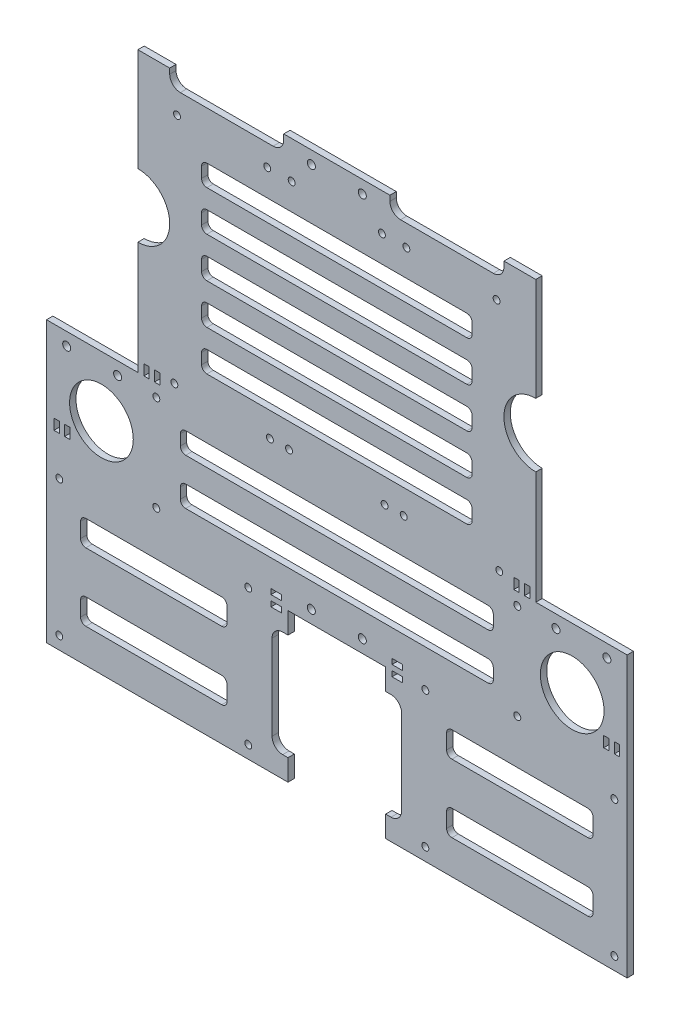
SolidWorks part; units mm, degrees
material "Oak"
ref_plane "Front Plane" through (0, 0, 0) normal (0, 0, 1) x (1, 0, 0)
ref_plane "Top Plane" through (0, 0, 0) normal (0, 1, 0) x (1, 0, 0)
ref_plane "Right Plane" through (0, 0, 0) normal (1, 0, 0) x (0, 0, -1)
sketch "Sketch1" plane through (0, 0, 0) normal (0, 0, 1) x (1, 0, 0)
  line L1 (0, 0) -> (273.4, 0)
  line L2 (0, 0) -> (0, -263.4)
  line L3 (0, -263.4) -> (273.4, -263.4)
  line L4 (273.4, 0) -> (273.4, -263.4)
  dimension "D1" = 273.4
  dimension "D2" = 263.4
extrude "Boss-Extrude1" add sketch "Sketch1" along normal blind 3
sketch "Sketch2" plane through (0, 0, 3) normal (0, 0, 1) x (1, 0, 0)
  line L1 (0, 0) -> (43, 0)
  line L2 (0, 0) -> (0, -131.64)
  line L3 (0, -131.64) -> (43, -131.64)
  line L4 (43, 0) -> (43, -131.64)
  line L9 (273.4, 0) -> (230.4, 0)
  line L10 (273.4, 0) -> (273.4, -131.64)
  line L11 (273.4, -131.64) -> (230.4, -131.64)
  line L12 (230.4, 0) -> (230.4, -131.64)
  dimension "D1" = 43
  dimension "D2" = 131.64
  dimension "D5" = 43
  dimension "D6" = 131.64
extrude "Cut-Extrude1" cut sketch "Sketch2" against normal through all
sketch "Sketch3" plane through (0, 0, 0) normal (0, 0, -1) x (-1, 0, 0)
  line L0 (0, -263.4) -> (-273.4, -263.4) construction
  line L1 (-159.7, -193.4) -> (-113.7, -193.4)
  line L2 (-159.7, -193.4) -> (-159.7, -263.4)
  line L3 (-159.7, -263.4) -> (-113.7, -263.4)
  line L4 (-113.7, -193.4) -> (-113.7, -263.4)
  line L5 (-273.4, -263.4) -> (-273.4, -131.64) construction
  dimension "D1" = 46
  dimension "D2" = 70
  dimension "D3" = 113.7
extrude "Cut-Extrude2" cut sketch "Sketch3" against normal through all
hole_wizard "#4 Clearance Hole1" positions "Sketch5" profile "Sketch6" hole size "#4" standard "ANSI Inch" end condition up to next
sketch "Sketch5" plane through (0, 0, 0) normal (0, 0, -1) x (-1, 0, 0)
  line L4 (-159.7, -263.4) -> (-273.4, -263.4) construction
  line L8 (-221.7, -137.5) -> (-51.7, -137.5) construction
  line L9 (-221.7, -137.5) -> (-221.7, -182.5) construction
  line L10 (-221.7, -182.5) -> (-51.7, -182.5) construction
  line L11 (-51.7, -137.5) -> (-51.7, -182.5) construction
  line L31 (-157.95, -17.5) -> (-115.45, -17.5) construction
  line L32 (-159.2, -127.5) -> (-114.2, -127.5) construction
  line L35 (-136.7, 0) -> (-136.7, -193.4) construction
  line L36 (-230.4, 0) -> (-43, 0) construction
  line L37 (-113.7, -193.4) -> (-159.7, -193.4) construction
  line L38 (-103.95, -17.5) -> (-61.45, -17.5) construction
  line L39 (-105.2, -127.5) -> (-60.2, -127.5) construction
  line L40 (-211.95, -17.5) -> (-169.45, -17.5) construction
  line L41 (-213.2, -127.5) -> (-168.2, -127.5) construction
  line L42 (0, -131.64) -> (0, -263.4) construction
  line L43 (-273.4, -263.4) -> (-273.4, -131.64) construction
  point P0 (-267.4, -257.4)
  point P2 (-267.4, -193.4)
  point P4 (-178.4, -193.4)
  point P6 (-178.4, -257.4)
  point P8 (-95, -257.4)
  point P10 (-95, -193.4)
  point P12 (-6, -193.4)
  point P14 (-6, -257.4)
  point P16 (-221.7, -137.5)
  point P18 (-221.7, -182.5)
  point P20 (-51.7, -137.5)
  point P22 (-51.7, -182.5)
  point P276 (-115.45, -17.5)
  point P277 (-157.95, -17.5)
  point P278 (-114.2, -127.5)
  point P279 (-159.2, -127.5)
  point P302 (-136.7, -17.5)
  point P306 (-136.7, -127.5)
  point P311 (-61.45, -17.5)
  point P312 (-103.95, -17.5)
  point P313 (-60.2, -127.5)
  point P314 (-105.2, -127.5)
  point P320 (-169.45, -17.5)
  point P321 (-211.95, -17.5)
  point P322 (-168.2, -127.5)
  point P323 (-213.2, -127.5)
  point P330 (-136.7, -137.5)
  dimension "D1" = 89
  dimension "D2" = 6
  dimension "D3" = 64
  dimension "D4" = 6
  dimension "D5" = 89
  dimension "D6" = 64
  dimension "D7" = 6
  dimension "D8" = 45
  dimension "D9" = 170
  dimension "D10" = 42.5
  dimension "D11" = 45
  dimension "D12" = 110
  dimension "D13" = 17.5
  dimension "D14" = 2
  dimension "D15" = 10
sketch "Sketch6" plane through (267.4, -257.4, 0) normal (1, 0, 0) x (0, 1, 0)
  line L0 (0, 0) -> (0, 3)
  line L1 (0, 3) -> (1.6319, 3)
  line L2 (1.6319, 3) -> (1.632, 0)
  line L5 (1.632, 0) -> (0, 0)
  line L11 (0, -6.35) -> (0, 107.95) construction
  dimension "Thru Hole Dia." = 3.2639
  dimension "Thru Hole Depth" = 3
sketch "Sketch4" plane through (0, 0, 3) normal (0, 0, 1) x (1, 0, 0)
  line L0 (230.4, 0) -> (43, 0) construction
  line L1 (58, 0) -> (111.7, 0)
  line L2 (58, 0) -> (58, -2.5)
  line L3 (63, -7.5) -> (106.7, -7.5)
  line L4 (111.7, 0) -> (111.7, -2.5)
  line L6 (43, -131.64) -> (43, 0) construction
  line L7 (159.7, -193.4) -> (159.7, -263.4) construction
  line L13 (0, -131.64) -> (0, -263.4) construction
  line L15 (43, -48.5) -> (43, -78.5)
  line L16 (230.4, -48.5) -> (230.4, -78.5)
  line L17 (210.4, -7.5) -> (166.7, -7.5)
  line L18 (161.7, 0) -> (161.7, -2.5)
  line L19 (215.4, 0) -> (161.7, 0)
  line L20 (215.4, 0) -> (215.4, -2.5)
  line L21 (51.7, -137.5) -> (51.7, -182.5) construction
  line L22 (51.7, -160) -> (0, -160) construction
  line L23 (159.7, -203.4) -> (162.2, -203.4)
  line L24 (159.7, -203.4) -> (159.7, -253.4)
  line L25 (159.7, -253.4) -> (162.2, -253.4)
  line L26 (167.2, -208.4) -> (167.2, -248.4)
  line L27 (159.7, -263.4) -> (273.4, -263.4) construction
  line L28 (136.7, -193.4) -> (136.7, -263.4411) construction
  line L29 (113.7, -193.4) -> (159.7, -193.4) construction
  line L30 (106.2, -208.4) -> (106.2, -248.4)
  line L31 (113.7, -253.4) -> (111.2, -253.4)
  line L32 (113.7, -203.4) -> (113.7, -253.4)
  line L33 (113.7, -203.4) -> (111.2, -203.4)
  line L34 (113.7, -263.4) -> (113.7, -193.4) construction
  line L35 (105.7, -195.9) -> (110.7, -195.9)
  line L36 (105.7, -195.9) -> (105.7, -193.4)
  line L37 (105.7, -193.4) -> (110.7, -193.4)
  line L38 (110.7, -195.9) -> (110.7, -193.4)
  line L39 (105.7, -190.9) -> (110.7, -190.9)
  line L40 (105.7, -190.9) -> (105.7, -188.4)
  line L41 (105.7, -188.4) -> (110.7, -188.4)
  line L42 (110.7, -190.9) -> (110.7, -188.4)
  line L51 (162.7, -190.9) -> (162.7, -188.4)
  line L52 (167.7, -188.4) -> (162.7, -188.4)
  line L53 (167.7, -190.9) -> (167.7, -188.4)
  line L54 (167.7, -190.9) -> (162.7, -190.9)
  line L55 (162.7, -195.9) -> (162.7, -193.4)
  line L56 (167.7, -193.4) -> (162.7, -193.4)
  line L57 (167.7, -195.9) -> (167.7, -193.4)
  line L58 (167.7, -195.9) -> (162.7, -195.9)
  line L64 (262.4, -170) -> (262.4, -175)
  line L69 (3.5, -170) -> (6, -170)
  line L70 (3.5, -170) -> (3.5, -175)
  line L71 (3.5, -175) -> (6, -175)
  line L72 (6, -170) -> (6, -175)
  line L73 (8.5, -170) -> (11, -170)
  line L74 (8.5, -170) -> (8.5, -175)
  line L75 (8.5, -175) -> (11, -175)
  line L76 (11, -170) -> (11, -175)
  line L77 (264.9, -175) -> (262.4, -175)
  line L78 (264.9, -170) -> (264.9, -175)
  line L79 (264.9, -170) -> (262.4, -170)
  line L80 (267.4, -170) -> (267.4, -175)
  line L81 (269.9, -175) -> (267.4, -175)
  line L82 (269.9, -170) -> (269.9, -175)
  line L83 (269.9, -170) -> (267.4, -170)
  line L84 (45.8282, -126.64) -> (48.3282, -126.64)
  line L85 (45.8282, -126.64) -> (45.8282, -131.64)
  line L86 (45.8282, -131.64) -> (48.3282, -131.64)
  line L87 (48.3282, -126.64) -> (48.3282, -131.64)
  line L88 (50.8282, -126.64) -> (53.3282, -126.64)
  line L89 (50.8282, -126.64) -> (50.8282, -131.64)
  line L90 (50.8282, -131.64) -> (53.3282, -131.64)
  line L91 (53.3282, -126.64) -> (53.3282, -131.64)
  line L92 (0, -131.64) -> (43, -131.64) construction
  line L93 (220.0718, -126.64) -> (220.0718, -131.64)
  line L94 (222.5718, -131.64) -> (220.0718, -131.64)
  line L95 (222.5718, -126.64) -> (222.5718, -131.64)
  line L96 (222.5718, -126.64) -> (220.0718, -126.64)
  line L97 (225.0718, -126.64) -> (225.0718, -131.64)
  line L98 (227.5718, -131.64) -> (225.0718, -131.64)
  line L99 (227.5718, -126.64) -> (227.5718, -131.64)
  line L100 (227.5718, -126.64) -> (225.0718, -126.64)
  arc A0 (43, -48.5) -> (43, -78.5) centre (43, -63.5) cw
  circle A1 centre (25.85, -160) radius 15
  circle A2 centre (247.55, -160) radius 15
  arc A3 (230.4, -48.5) -> (230.4, -78.5) centre (230.4, -63.5) ccw
  arc A4 (58, -2.5) -> (63, -7.5) centre (63, -2.5) ccw
  arc A5 (106.7, -7.5) -> (111.7, -2.5) centre (106.7, -2.5) ccw
  arc A6 (166.7, -7.5) -> (161.7, -2.5) centre (166.7, -2.5) cw
  arc A7 (210.4, -7.5) -> (215.4, -2.5) centre (210.4, -2.5) ccw
  arc A10 (162.2, -253.4) -> (167.2, -248.4) centre (162.2, -248.4) ccw
  arc A11 (162.2, -203.4) -> (167.2, -208.4) centre (162.2, -208.4) cw
  arc A12 (111.2, -203.4) -> (106.2, -208.4) centre (111.2, -208.4) ccw
  arc A13 (111.2, -253.4) -> (106.2, -248.4) centre (111.2, -248.4) cw
  point P39 (58, -7.5)
  point P42 (111.7, -7.5)
  point P45 (161.7, -7.5)
  point P48 (215.4, -7.5)
  point P54 (167.2, -203.4)
  point P67 (106.2, -203.4)
  dimension "D4" = 5
  dimension "D7" = 15
  dimension "D8" = 30
  dimension "D5" = 2.5
  dimension "D10" = 5
  dimension "D1" = 7.5
  dimension "D2" = 15
  dimension "D3" = 50
  dimension "D6" = 63.5
  dimension "D9" = 10
  dimension "D11" = 2.5
  dimension "D12" = 2.5
  dimension "D13" = 5
  dimension "D14" = 3
  dimension "D15" = 2.5
  dimension "D16" = 2.5
  dimension "D17" = 2.5
  dimension "D18" = 5
  dimension "D19" = 3.5
  dimension "D20" = 2.5
extrude "Cut-Extrude3" cut sketch "Sketch4" against normal up to next
hole_wizard "#6 Clearance Hole1" positions "Sketch7" profile "Sketch8" hole size "#6" standard "ANSI Inch" end condition up to next
sketch "Sketch7" plane through (0, 0, 3) normal (0, 0, 1) x (1, 0, 0)
  line L1 (111.7, -2.5) -> (111.7, 0) construction
  line L4 (113.7, -263.4) -> (113.7, -253.4) construction
  line L5 (0, -131.64) -> (43, -131.64) construction
  line L6 (113.7, -193.4) -> (159.7, -193.4) construction
  line L7 (230.4, -131.64) -> (273.4, -131.64) construction
  line L8 (161.7, 0) -> (111.7, 0) construction
  line L9 (0, -131.64) -> (0, -263.4) construction
  line L10 (273.4, -263.4) -> (273.4, -131.64) construction
  point P0 (124.7, -6)
  point P2 (148.7, -6)
  point P4 (9.5, -137.64)
  point P6 (33.5, -137.64)
  point P8 (124.7, -187.4)
  point P10 (148.7, -187.4)
  point P20 (263.9, -137.64)
  point P22 (239.9, -137.64)
  dimension "D1" = 24
  dimension "D2" = 24
  dimension "D3" = 24
  dimension "D4" = 24
  dimension "D5" = 13
  dimension "D6" = 11
  dimension "D7" = 6
  dimension "D8" = 6
  dimension "D9" = 6
  dimension "D10" = 6
  dimension "D11" = 9.5
  dimension "D12" = 9.5
sketch "Sketch8" plane through (124.7, -6, 3) normal (1, 0, 0) x (0, -1, 0)
  line L0 (0, 0) -> (0, 3)
  line L1 (0, 3) -> (1.8986, 3)
  line L2 (1.8986, 3) -> (1.8986, 0)
  line L5 (1.8986, 0) -> (0, 0)
  line L11 (0, -6.35) -> (0, 107.95) construction
  dimension "Thru Hole Dia." = 3.7973
  dimension "Thru Hole Depth" = 3
sketch "Sketch10" plane through (0, 0, 3) normal (0, 0, 1) x (1, 0, 0)
  line L0 (43, -48.5) -> (43, 0) construction
  line L1 (75.5, -30) -> (197.9, -30)
  line L2 (73, -32.5) -> (73, -37.5)
  line L3 (75.5, -40) -> (197.9, -40)
  line L4 (200.4, -32.5) -> (200.4, -37.5)
  line L5 (230.4, 0) -> (230.4, -48.5) construction
  line L6 (161.7, 0) -> (111.7, 0) construction
  line L7 (73, -51.5) -> (73, -56.5)
  line L8 (75.5, -49) -> (197.9, -49)
  line L9 (200.4, -51.5) -> (200.4, -56.5)
  line L10 (75.5, -59) -> (197.9, -59)
  line L11 (73, -70.5) -> (73, -75.5)
  line L12 (75.5, -68) -> (197.9, -68)
  line L13 (200.4, -70.5) -> (200.4, -75.5)
  line L14 (75.5, -78) -> (197.9, -78)
  line L15 (73, -89.5) -> (73, -94.5)
  line L16 (75.5, -87) -> (197.9, -87)
  line L17 (200.4, -89.5) -> (200.4, -94.5)
  line L18 (75.5, -97) -> (197.9, -97)
  line L19 (73, -108.5) -> (73, -113.5)
  line L20 (75.5, -106) -> (197.9, -106)
  line L21 (200.4, -108.5) -> (200.4, -113.5)
  line L22 (75.5, -116) -> (197.9, -116)
  line L23 (73, -32.5) -> (73, -51.5) construction
  line L24 (43, -131.64) -> (43, -78.5) construction
  line L25 (18.5, -203.4) -> (82.5, -203.4)
  line L26 (16, -205.9) -> (16, -212.9)
  line L27 (18.5, -215.4) -> (82.5, -215.4)
  line L28 (85, -205.9) -> (85, -212.9)
  line L29 (65.5, -144.14) -> (207.9, -144.14)
  line L30 (63, -146.64) -> (63, -151.64)
  line L31 (65.5, -154.14) -> (207.9, -154.14)
  line L32 (210.4, -146.64) -> (210.4, -151.64)
  line L33 (230.4, -78.5) -> (230.4, -131.64) construction
  line L34 (0, -131.64) -> (43, -131.64) construction
  line L35 (51.7, -137.5) -> (51.7, -182.5) construction
  line L36 (51.7, -160) -> (225.1949, -160) construction
  line L37 (65.5, -165.86) -> (207.9, -165.86)
  line L38 (210.4, -173.36) -> (210.4, -168.36)
  line L39 (65.5, -175.86) -> (207.9, -175.86)
  line L40 (63, -173.36) -> (63, -168.36)
  line L41 (6, -193.4) -> (95, -193.4) construction
  line L42 (95, -193.4) -> (95, -257.4) construction
  line L43 (95, -257.4) -> (6, -257.4) construction
  line L44 (6, -257.4) -> (6, -193.4) construction
  line L45 (6, -225.4) -> (95, -225.4) construction
  line L46 (18.5, -235.4) -> (82.5, -235.4)
  line L47 (85, -244.9) -> (85, -237.9)
  line L48 (18.5, -247.4) -> (82.5, -247.4)
  line L49 (16, -244.9) -> (16, -237.9)
  line L50 (136.7, -193.4) -> (136.7, -279.5372) construction
  line L51 (113.7, -193.4) -> (159.7, -193.4) construction
  line L52 (254.9, -215.4) -> (190.9, -215.4)
  line L53 (188.4, -205.9) -> (188.4, -212.9)
  line L54 (254.9, -203.4) -> (190.9, -203.4)
  line L55 (257.4, -205.9) -> (257.4, -212.9)
  line L56 (257.4, -244.9) -> (257.4, -237.9)
  line L57 (254.9, -247.4) -> (190.9, -247.4)
  line L58 (188.4, -244.9) -> (188.4, -237.9)
  line L59 (254.9, -235.4) -> (190.9, -235.4)
  arc A0 (197.9, -30) -> (200.4, -32.5) centre (197.9, -32.5) cw
  arc A1 (197.9, -40) -> (200.4, -37.5) centre (197.9, -37.5) ccw
  arc A2 (73, -37.5) -> (75.5, -40) centre (75.5, -37.5) ccw
  arc A3 (75.5, -30) -> (73, -32.5) centre (75.5, -32.5) ccw
  arc A4 (75.5, -49) -> (73, -51.5) centre (75.5, -51.5) ccw
  arc A5 (73, -56.5) -> (75.5, -59) centre (75.5, -56.5) ccw
  arc A6 (197.9, -49) -> (200.4, -51.5) centre (197.9, -51.5) cw
  arc A7 (197.9, -59) -> (200.4, -56.5) centre (197.9, -56.5) ccw
  arc A8 (75.5, -68) -> (73, -70.5) centre (75.5, -70.5) ccw
  arc A9 (73, -75.5) -> (75.5, -78) centre (75.5, -75.5) ccw
  arc A10 (197.9, -68) -> (200.4, -70.5) centre (197.9, -70.5) cw
  arc A11 (197.9, -78) -> (200.4, -75.5) centre (197.9, -75.5) ccw
  arc A12 (75.5, -87) -> (73, -89.5) centre (75.5, -89.5) ccw
  arc A13 (73, -94.5) -> (75.5, -97) centre (75.5, -94.5) ccw
  arc A14 (197.9, -87) -> (200.4, -89.5) centre (197.9, -89.5) cw
  arc A15 (197.9, -97) -> (200.4, -94.5) centre (197.9, -94.5) ccw
  arc A16 (75.5, -106) -> (73, -108.5) centre (75.5, -108.5) ccw
  arc A17 (73, -113.5) -> (75.5, -116) centre (75.5, -113.5) ccw
  arc A18 (197.9, -106) -> (200.4, -108.5) centre (197.9, -108.5) cw
  arc A19 (197.9, -116) -> (200.4, -113.5) centre (197.9, -113.5) ccw
  arc A20 (63, -151.64) -> (65.5, -154.14) centre (65.5, -151.64) ccw
  arc A21 (207.9, -154.14) -> (210.4, -151.64) centre (207.9, -151.64) ccw
  arc A22 (207.9, -144.14) -> (210.4, -146.64) centre (207.9, -146.64) cw
  arc A23 (65.5, -144.14) -> (63, -146.64) centre (65.5, -146.64) ccw
  arc A24 (207.9, -165.86) -> (210.4, -168.36) centre (207.9, -168.36) cw
  arc A25 (207.9, -175.86) -> (210.4, -173.36) centre (207.9, -173.36) ccw
  arc A26 (63, -168.36) -> (65.5, -165.86) centre (65.5, -168.36) cw
  arc A27 (65.5, -175.86) -> (63, -173.36) centre (65.5, -173.36) cw
  arc A28 (16, -212.9) -> (18.5, -215.4) centre (18.5, -212.9) ccw
  arc A29 (82.5, -215.4) -> (85, -212.9) centre (82.5, -212.9) ccw
  arc A30 (85, -205.9) -> (82.5, -203.4) centre (82.5, -205.9) ccw
  arc A31 (18.5, -203.4) -> (16, -205.9) centre (18.5, -205.9) ccw
  arc A32 (82.5, -235.4) -> (85, -237.9) centre (82.5, -237.9) cw
  arc A33 (85, -244.9) -> (82.5, -247.4) centre (82.5, -244.9) cw
  arc A34 (16, -237.9) -> (18.5, -235.4) centre (18.5, -237.9) cw
  arc A35 (18.5, -247.4) -> (16, -244.9) centre (18.5, -244.9) cw
  arc A36 (190.9, -215.4) -> (188.4, -212.9) centre (190.9, -212.9) cw
  arc A37 (188.4, -205.9) -> (190.9, -203.4) centre (190.9, -205.9) cw
  arc A38 (257.4, -212.9) -> (254.9, -215.4) centre (254.9, -212.9) cw
  arc A39 (254.9, -203.4) -> (257.4, -205.9) centre (254.9, -205.9) cw
  arc A40 (257.4, -237.9) -> (254.9, -235.4) centre (254.9, -237.9) ccw
  arc A41 (254.9, -247.4) -> (257.4, -244.9) centre (254.9, -244.9) ccw
  arc A42 (188.4, -244.9) -> (190.9, -247.4) centre (190.9, -244.9) ccw
  arc A43 (190.9, -235.4) -> (188.4, -237.9) centre (190.9, -237.9) ccw
  dimension "D4" = 2.5
  dimension "D8" = 2.5
  dimension "D13" = 2.5
  dimension "D1" = 10
  dimension "D2" = 30
  dimension "D3" = 30
  dimension "D5" = 30
  dimension "D7" = 19
  dimension "D9" = 20
  dimension "D10" = 20
  dimension "D11" = 10
  dimension "D12" = 12.5
  dimension "D14" = 10
  dimension "D15" = 10
  dimension "D16" = 10
  dimension "D17" = 10
  dimension "D6" = 5
extrude "Cut-Extrude4" cut sketch "Sketch10" against normal up to next
